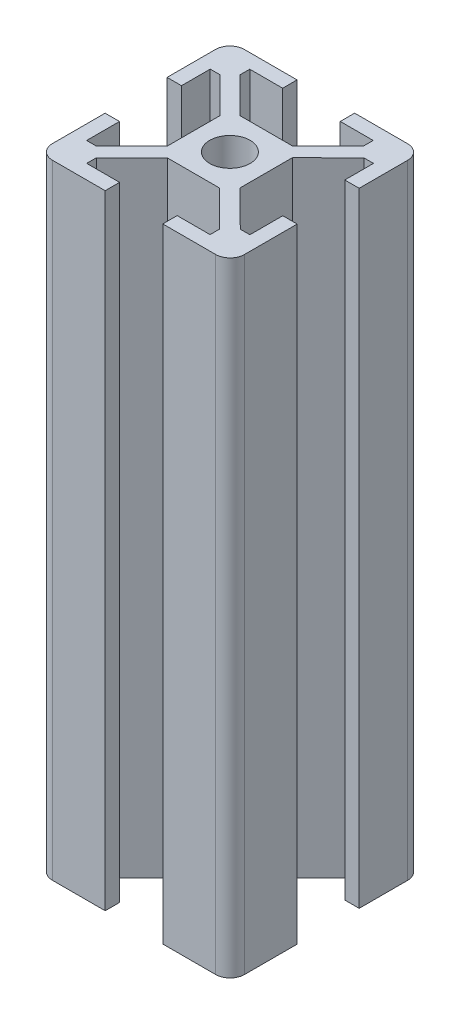
SolidWorks part; units mm, degrees
material "6063-O, Extruded Rod (SS)"
ref_plane "Front Plane" through (0, 0, 0) normal (0, 0, 1) x (1, 0, 0)
ref_plane "Top Plane" through (0, 0, 0) normal (0, 1, 0) x (1, 0, 0)
ref_plane "Right Plane" through (0, 0, 0) normal (1, 0, 0) x (0, 0, -1)
sketch "Sketch1" plane through (0, 0, 0) normal (0, 1, 0) x (1, 0, 0)
  line L0 (0, 0) -> (7, 0)
  line L1 (0, 0) -> (20.0186, 0) construction
  line L2 (0, 0) -> (0, 20) construction
  line L3 (0, 20) -> (20.0186, 20) construction
  line L4 (20.0186, 0) -> (20.0186, 20) construction
  line L5 (7, 0) -> (7, 1.5)
  line L6 (7, 1.5) -> (3.569, 1.5)
  line L7 (3.569, 1.5) -> (3.569, 2.5)
  line L8 (3.569, 2.5) -> (7.269, 6.2)
  line L9 (12.731, 6.2) -> (16.431, 2.5)
  line L10 (16.431, 2.5) -> (16.431, 1.5)
  line L11 (13, 1.5) -> (13, 0)
  line L12 (10, 22.1076) -> (10, -4.4713) construction
  line L20 (13, 0) -> (20.0186, 0)
  line L21 (20.0186, 0) -> (20.0186, 6.9935)
  line L22 (20.0186, 6.9935) -> (18.5186, 6.9935)
  line L23 (18.5186, 6.9935) -> (18.5186, 3.5625)
  line L24 (18.5186, 3.5625) -> (17.5186, 3.5625)
  line L28 (17.5186, 16.4477) -> (18.5186, 16.4477)
  line L29 (18.5186, 16.4477) -> (18.5186, 13.4532)
  line L30 (18.5186, 13.4532) -> (20.0186, 13.4532)
  line L31 (20.0186, 13.4532) -> (20.0186, 20)
  line L32 (20.0186, 20) -> (13, 20)
  line L43 (13, 20) -> (13, 18.5)
  line L44 (13, 18.5) -> (16.431, 18.5)
  line L45 (16.431, 18.5) -> (16.431, 17.5)
  line L46 (16.431, 17.5) -> (12.731, 13.7958)
  line L47 (12.731, 13.7958) -> (7.269, 13.7958)
  line L48 (7.269, 13.7958) -> (3.569, 17.5)
  line L49 (3.569, 17.5) -> (3.569, 18.5)
  line L50 (3.569, 18.5) -> (7, 18.5)
  line L51 (7, 18.5) -> (7, 20)
  line L52 (7, 20) -> (0, 20)
  line L53 (0, 20) -> (0, 13.4532)
  line L54 (0, 13.4532) -> (1.5, 13.4532)
  line L55 (1.5, 13.4532) -> (1.5, 16.4477)
  line L56 (7.269, 6.2) -> (12.731, 6.2)
  line L58 (16.431, 1.5) -> (13, 1.5)
  line L60 (20.0186, 10) -> (7.5374, 10) construction
  line L62 (1.5, 16.4477) -> (2.5, 16.4477)
  line L63 (2.5, 16.4477) -> (6.2095, 12.734)
  line L64 (6.2095, 12.734) -> (6.2095, 7.272)
  line L65 (6.2095, 7.272) -> (2.5, 3.5625)
  line L66 (2.5, 3.5625) -> (1.5, 3.5625)
  line L67 (1.5, 3.5625) -> (1.5, 6.9935)
  line L68 (1.5, 6.9935) -> (0, 6.9935)
  line L69 (0, 6.9935) -> (0, 0)
  line L70 (17.5186, 16.4477) -> (13.778, 12.731)
  line L71 (13.778, 12.731) -> (13.778, 7.269)
  line L72 (13.778, 7.269) -> (17.5186, 3.5625)
  circle A0 centre (10, 10) radius 2.1
  point P66 (10, 6.2)
  point P85 (13.778, 10)
  dimension "D6" = 4.2
  dimension "D7" = 45
  dimension "D2" = 20
  dimension "D3" = 6
  dimension "D4" = 1.5
  dimension "D5" = 6.2
  dimension "D8" = 1.5
  dimension "D9" = 1
extrude "Boss-Extrude1" add sketch "Sketch1" along normal blind 65
fillet "Fillet1" radius 1.5 4 edges at (0, 32.5, 0) (0, 32.5, -20) (20.0186, 32.5, 0) (20.0186, 32.5, -20)
